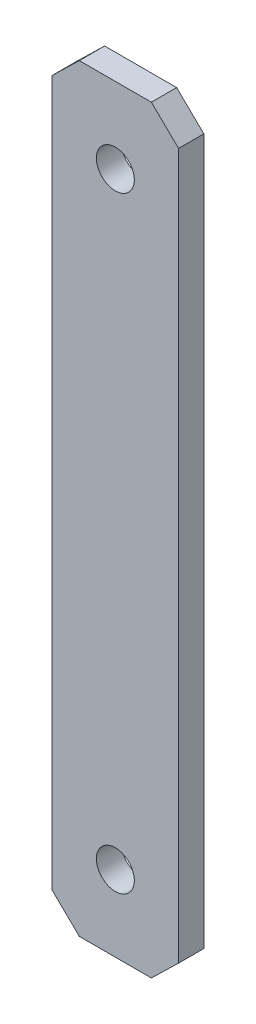
SolidWorks part; units mm, degrees
ref_plane "Piano frontale" through (0, 0, 0) normal (0, 0, 1) x (1, 0, 0)
ref_plane "Piano superiore" through (0, 0, 0) normal (0, 1, 0) x (1, 0, 0)
ref_plane "Piano destro" through (0, 0, 0) normal (1, 0, 0) x (0, 0, -1)
sketch "Schizzo1" plane through (0, 0, 0) normal (0, 0, 1) x (1, 0, 0)
  line L0 (0, 55.8155) -> (2.15, 57.9078)
  line L1 (7.85, -2.0922) -> (2.15, -2.0922)
  line L2 (10, 0) -> (10, 55.8155)
  line L3 (7.85, 57.9078) -> (2.15, 57.9078)
  line L4 (0, 0) -> (0, 55.8155)
  line L7 (7.85, 57.9078) -> (10, 55.8155)
  line L8 (0, 0) -> (2.15, -2.0922)
  line L9 (7.85, -2.0922) -> (10, 0)
  point P0 (0, 0)
  dimension "D1" = 10
  dimension "D2" = 3
  dimension "D3" = 60
  dimension "D4" = 3
  dimension "D5" = 5.7
  dimension "D6" = 55.8155
  dimension "D7" = 55.8155
extrude "Estrusione-Estrusione1" add sketch "Schizzo1" against normal blind 2
sketch "Schizzo2" plane through (0, 0, 0) normal (0, 0, 1) x (1, 0, 0)
  line L0 (5, 57.9078) -> (5, -2.0922) construction
  line L1 (7.85, 57.9078) -> (2.15, 57.9078) construction
  line L2 (2.15, -2.0922) -> (7.85, -2.0922) construction
  circle A0 centre (5, 51.9078) radius 1.5
  circle A1 centre (5, 3.9078) radius 1.5
  dimension "D1" = 3
  dimension "D3" = 3
  dimension "D2" = 6
  dimension "D4" = 6
extrude "Taglio-Estrusione1" cut sketch "Schizzo2" against normal through all from surface at 0 starting at face at (5, 27.9078, 0)
